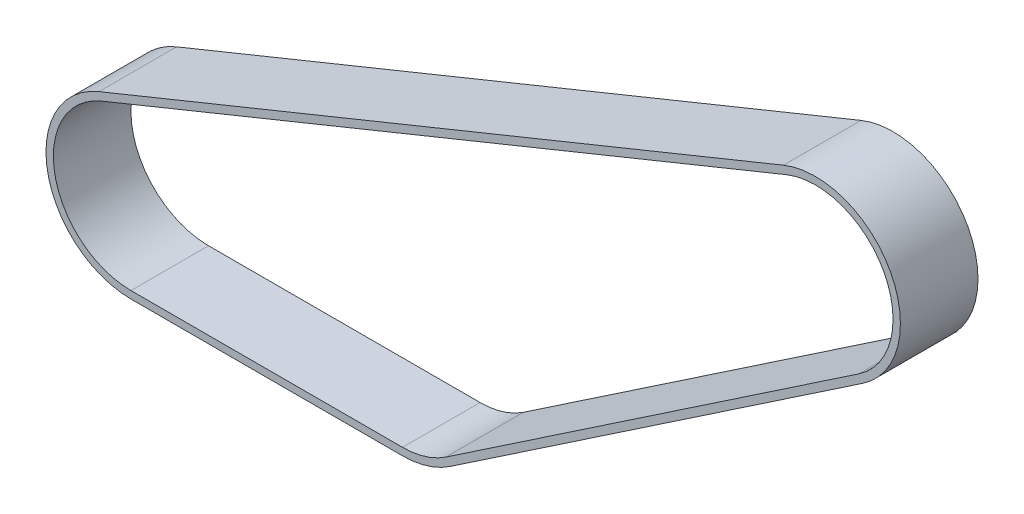
SolidWorks part; units mm, degrees
ref_plane "정면" through (0, 0, 0) normal (0, 0, 1) x (1, 0, 0)
ref_plane "윗면" through (0, 0, 0) normal (0, 1, 0) x (1, 0, 0)
ref_plane "우측면" through (0, 0, 0) normal (1, 0, 0) x (0, 0, -1)
sketch "스케치2" plane through (0, 0, 0) normal (0, 0, 1) x (1, 0, 0)
  line L0 (-220.5605, -139.7505) -> (-45.5605, -139.7505)
  line L1 (-239.406, -43.438) -> (201.7151, 136.063)
  line L2 (-17.6009, -131.2023) -> (248.5202, 48.2986)
  line L3 (-220.5605, -89.7505) -> (-45.5605, -89.7505) construction
  line L4 (220.5605, 89.7505) -> (220.5605, -89.7505) construction
  line L5 (-241.1971, -39.0364) -> (199.924, 140.4645)
  line L6 (-14.9436, -135.1419) -> (251.1775, 44.359)
  line L7 (-220.5605, -144.5025) -> (-45.5605, -144.5025)
  arc A0 (-239.406, -43.438) -> (-220.5605, -139.7505) centre (-220.5605, -89.7505) ccw
  arc A1 (248.5202, 48.2986) -> (201.7151, 136.063) centre (220.5605, 89.7505) ccw
  arc A2 (-45.5605, -139.7505) -> (-17.6009, -131.2023) centre (-45.5605, -89.7505) ccw
  arc A3 (251.1775, 44.359) -> (199.924, 140.4645) centre (220.5605, 89.7505) ccw
  arc A4 (-45.5605, -144.5025) -> (-14.9436, -135.1419) centre (-45.5605, -89.7505) ccw
  arc A5 (-241.1971, -39.0364) -> (-220.5605, -144.5025) centre (-220.5605, -89.7505) ccw
  dimension "D1" = 100
  dimension "D2" = 100
  dimension "D3" = 100
  dimension "D4" = 4.752
extrude "보스-돌출1" add sketch "스케치2" along normal blind 50
